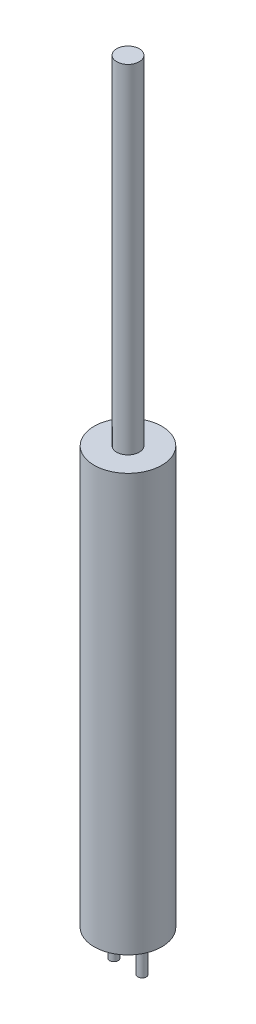
SolidWorks part; units mm, degrees
ref_plane "Front Plane" through (0, 0, 0) normal (0, 0, 1) x (1, 0, 0)
ref_plane "Top Plane" through (0, 0, 0) normal (0, 1, 0) x (1, 0, 0)
ref_plane "Right Plane" through (0, 0, 0) normal (1, 0, 0) x (0, 0, -1)
other "Configuration Table"
sketch "Sketch1" plane through (0, 0, 0) normal (0, 1, 0) x (1, 0, 0)
  circle A0 centre (-2.5, 0) radius 0.75
extrude "Pin_1" add sketch "Sketch1" along normal blind 6
sketch "Sketch2" plane through (0, 0, 0) normal (0, 1, 0) x (1, 0, 0)
  circle A0 centre (2.5, 0) radius 0.75
extrude "Pin_2" add sketch "Sketch2" along normal blind 6
sketch "Sketch3" plane through (0, 0, 0) normal (0, 1, 0) x (1, 0, 0)
  circle A0 centre (0, 0) radius 6
  dimension "D1" = 12
extrude "Body" add sketch "Sketch3" along normal blind 74 from offset 6
sketch "Sketch4" plane through (0, 0, 0) normal (0, 1, 0) x (1, 0, 0)
  circle A0 centre (0, 0) radius 2
extrude "Cable" add sketch "Sketch4" along normal blind 60 from offset 80
equation "\"tds_D\"= 12.0   'ASSUMPTION: TDS probe body OD (PDF fallback)"
equation "\"tds_L\"= 80.0   'ASSUMPTION: TDS probe length (PDF fallback)"
equation "\"cable_D\"= 4.0   'ASSUMPTION: Probe cable OD (designer choice)"
equation "\"D1@Sketch3\" = \"tds_D\""
